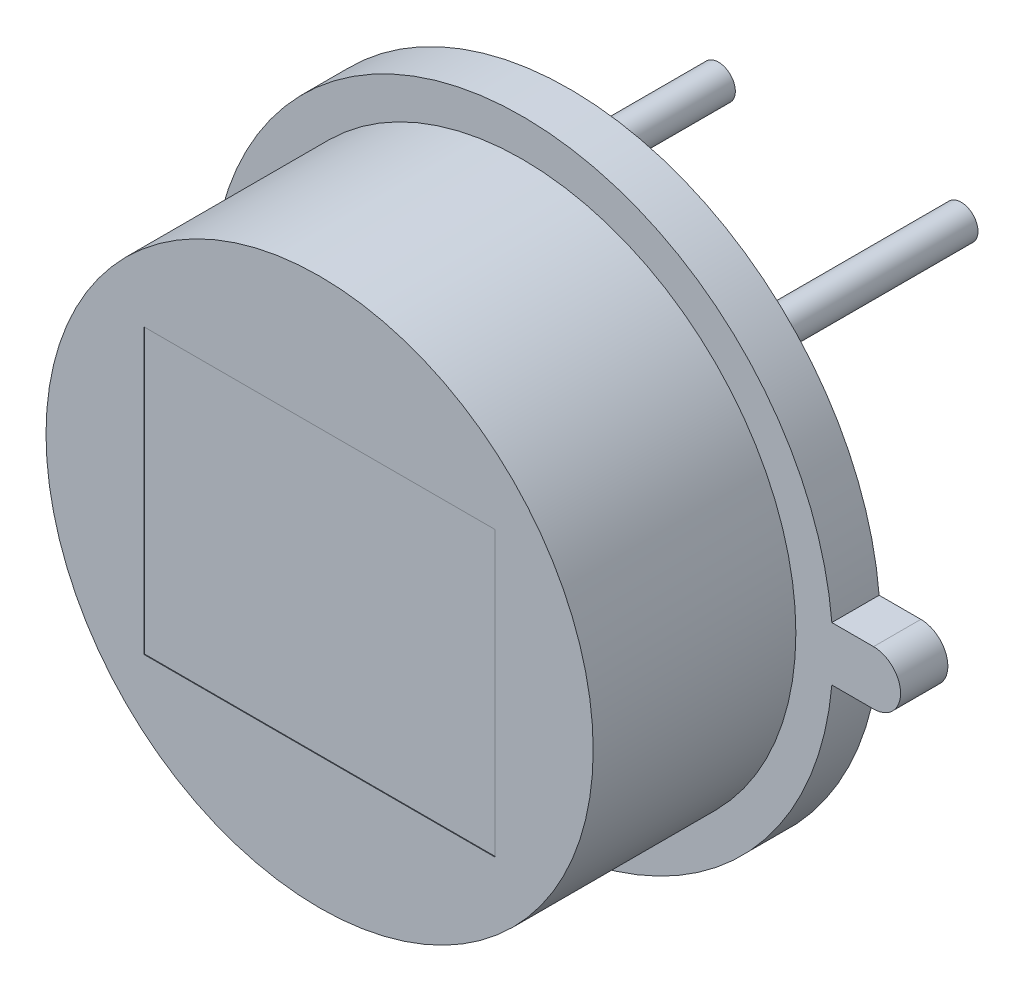
SolidWorks part; units mm, degrees
other "Детальный элемент1"
ref_plane "Спереди" through (0, 0, 0) normal (0, 0, 1) x (1, 0, 0)
ref_plane "Сверху" through (0, 0, 0) normal (0, 1, 0) x (1, 0, 0)
ref_plane "Справа" through (0, 0, 0) normal (1, 0, 0) x (0, 0, -1)
sketch "Эскиз1" plane through (0, 0, 0) normal (0, 0, 1) x (1, 0, 0)
  line L2 (5.2, 0.4) -> (4.5826, 0.4)
  line L4 (5.2, -0.4) -> (4.5826, -0.4)
  arc A1 (5.2, -0.4) -> (5.2, 0.4) centre (5.2, 0) ccw
  arc A3 (4.5826, 0.4) -> (4.5826, -0.4) centre (0, 0) ccw
  dimension "D1" = 4.6
  dimension "D2" = 0.8
  dimension "D3" = 5.2
extrude "Бобышка-Вытянуть1" add sketch "Эскиз1" along normal blind 0.7
sketch "Эскиз2" plane through (0, 0, 0.7) normal (0, 0, 1) x (1, 0, 0)
  circle A0 centre (0, 0) radius 4.05
  dimension "D1" = 8.1
extrude "Бобышка-Вытянуть2" add sketch "Эскиз2" along normal blind 3
sketch "Эскиз3" plane through (0, 0, 3.7) normal (0, 0, 1) x (1, 0, 0)
  line L1 (-2.6, -2.1) -> (2.6, -2.1)
  line L2 (-2.6, -2.1) -> (-2.6, 2.1)
  line L3 (-2.6, 2.1) -> (2.6, 2.1)
  line L4 (2.6, -2.1) -> (2.6, 2.1)
  line L5 (-2.6, -2.1) -> (2.6, 2.1) construction
  line L6 (-2.6, 2.1) -> (2.6, -2.1) construction
  point P0 (0, 0)
  dimension "D1" = 5.2
  dimension "D2" = 4.2
extrude "Вырез-Вытянуть1" cut sketch "Эскиз3" against normal blind 0.01
sketch "Эскиз4" plane through (0, 0, 0) normal (0, 0, 1) x (1, 0, 0)
  circle A1 centre (1.796, 1.796) radius 0.25
  circle A2 centre (-1.796, 1.796) radius 0.25
  circle A3 centre (-1.796, -1.796) radius 0.25
  point P8 (0, 0)
  dimension "D1" = 0.5
  dimension "D2" = 3.592
  dimension "D3" = 0.5
  dimension "D4" = 0.5
  dimension "D5" = 3.592
  dimension "D7" = 1.796
  dimension "D8" = 1.796
extrude "Бобышка-Вытянуть3" add sketch "Эскиз4" against normal blind 4
